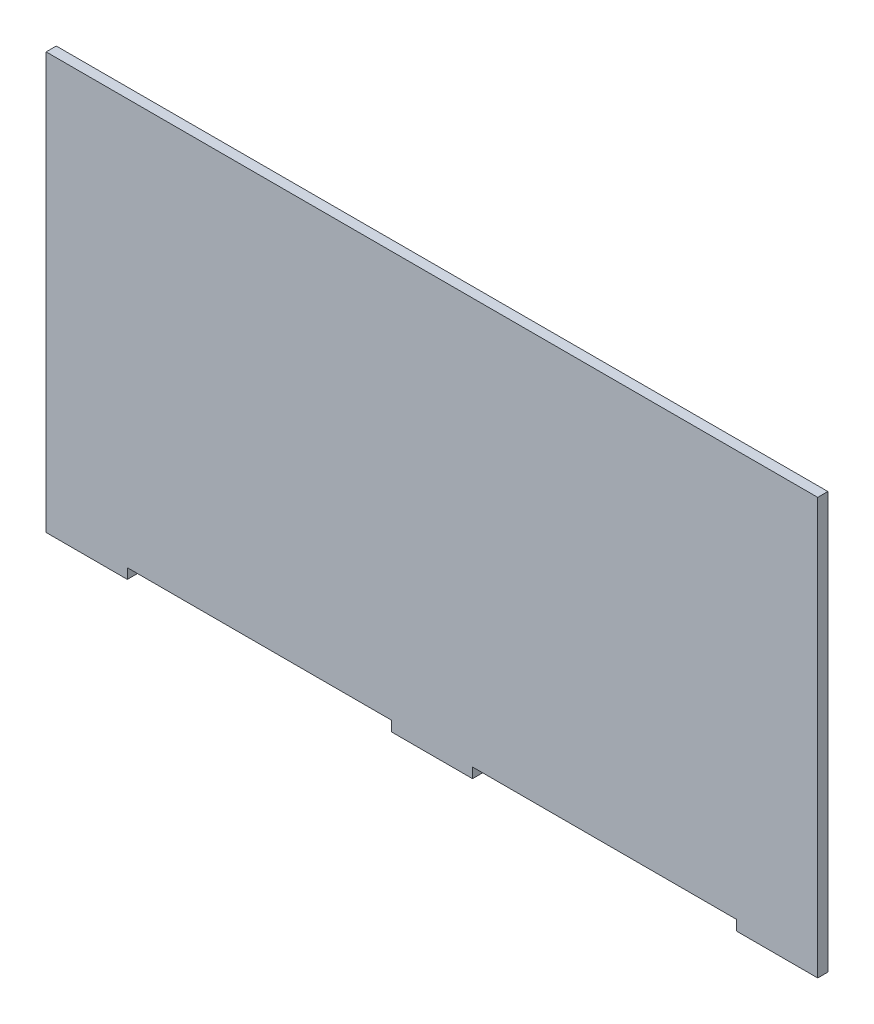
SolidWorks part; units mm, degrees
ref_plane "Plan de face" through (0, 0, 0) normal (0, 0, 1) x (1, 0, 0)
ref_plane "Plan de dessus" through (0, 0, 0) normal (0, 1, 0) x (1, 0, 0)
ref_plane "Plan de droite" through (0, 0, 0) normal (1, 0, 0) x (0, 0, -1)
sketch "Esquisse1" plane through (0, 0, 0) normal (0, 0, 1) x (1, 0, 0)
  line L0 (-39.4746, -50.57) -> (0.5254, -50.57)
  line L1 (0.5254, -50.57) -> (0.5254, -45.57)
  line L2 (0.5254, -45.57) -> (130.5254, -45.57)
  line L3 (130.5254, -45.57) -> (130.5254, -50.57)
  line L4 (130.5254, -50.57) -> (170.5254, -50.57)
  line L5 (170.5254, -50.57) -> (170.5254, -45.57)
  line L6 (-39.4746, -50.57) -> (-39.4746, 154.43)
  line L7 (170.5254, -45.57) -> (300.5254, -45.57)
  line L8 (300.5254, -45.57) -> (300.5254, -50.57)
  line L9 (300.5254, -50.57) -> (340.5254, -50.57)
  line L10 (340.5254, -50.57) -> (340.5254, 154.43)
  line L11 (340.5254, 154.43) -> (-39.4746, 154.43)
  point P9 (-112.0176, 134.7271)
  dimension "D1" = 205
  dimension "D2" = 205
  dimension "D3" = 40
  dimension "D4" = 130
  dimension "D5" = 40
  dimension "D6" = 130
  dimension "D7" = 40
  dimension "D8" = 5
  dimension "D9" = 5
  dimension "D10" = 5
  dimension "D11" = 5
extrude "Boss.-Extru.1" add sketch "Esquisse1" along normal blind 5
